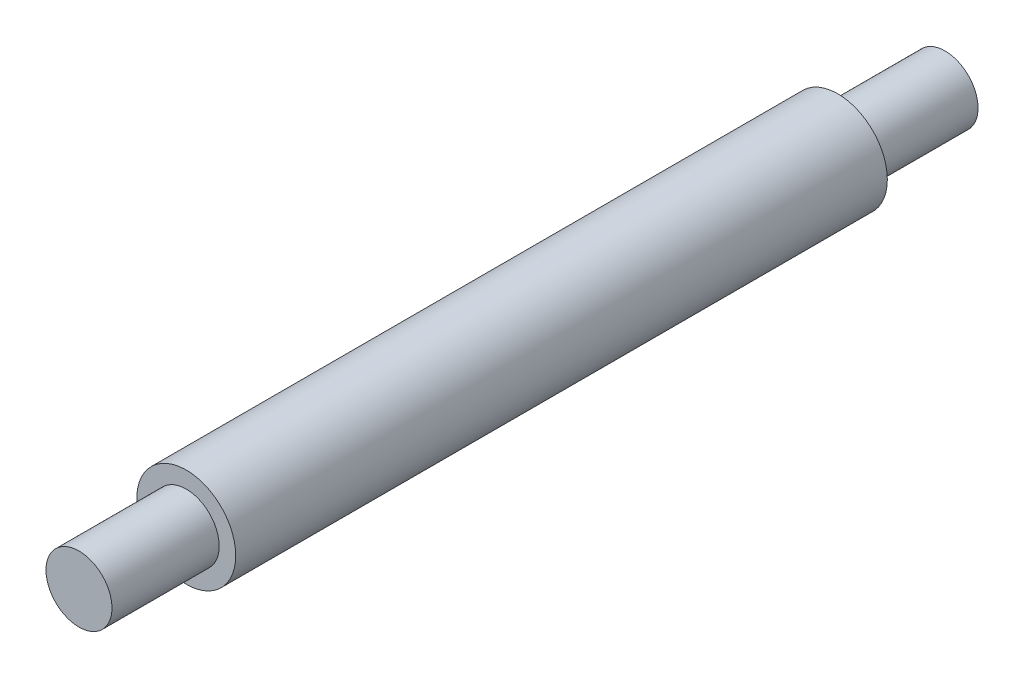
SolidWorks part; units mm, degrees
ref_plane "Front Plane" through (0, 0, 0) normal (0, 0, 1) x (1, 0, 0)
ref_plane "Top Plane" through (0, 0, 0) normal (0, 1, 0) x (1, 0, 0)
ref_plane "Right Plane" through (0, 0, 0) normal (1, 0, 0) x (0, 0, -1)
sketch "Sketch1" plane through (0, 0, 0) normal (0, 0, 1) x (1, 0, 0)
  circle A0 centre (0, 0) radius 4
  dimension "D1" = 8
extrude "Boss-Extrude1" add sketch "Sketch1" along normal blind 13
sketch "Sketch2" plane through (0, 0, 13) normal (0, 0, 1) x (1, 0, 0)
  circle A0 centre (0, 0) radius 6
  dimension "D1" = 12
extrude "Boss-Extrude2" add sketch "Sketch2" along normal blind 79
sketch "Sketch3" plane through (0, 0, 92) normal (0, 0, 1) x (1, 0, 0)
  circle A0 centre (0, 0) radius 4
  dimension "D1" = 8
extrude "Boss-Extrude3" add sketch "Sketch3" along normal blind 13
